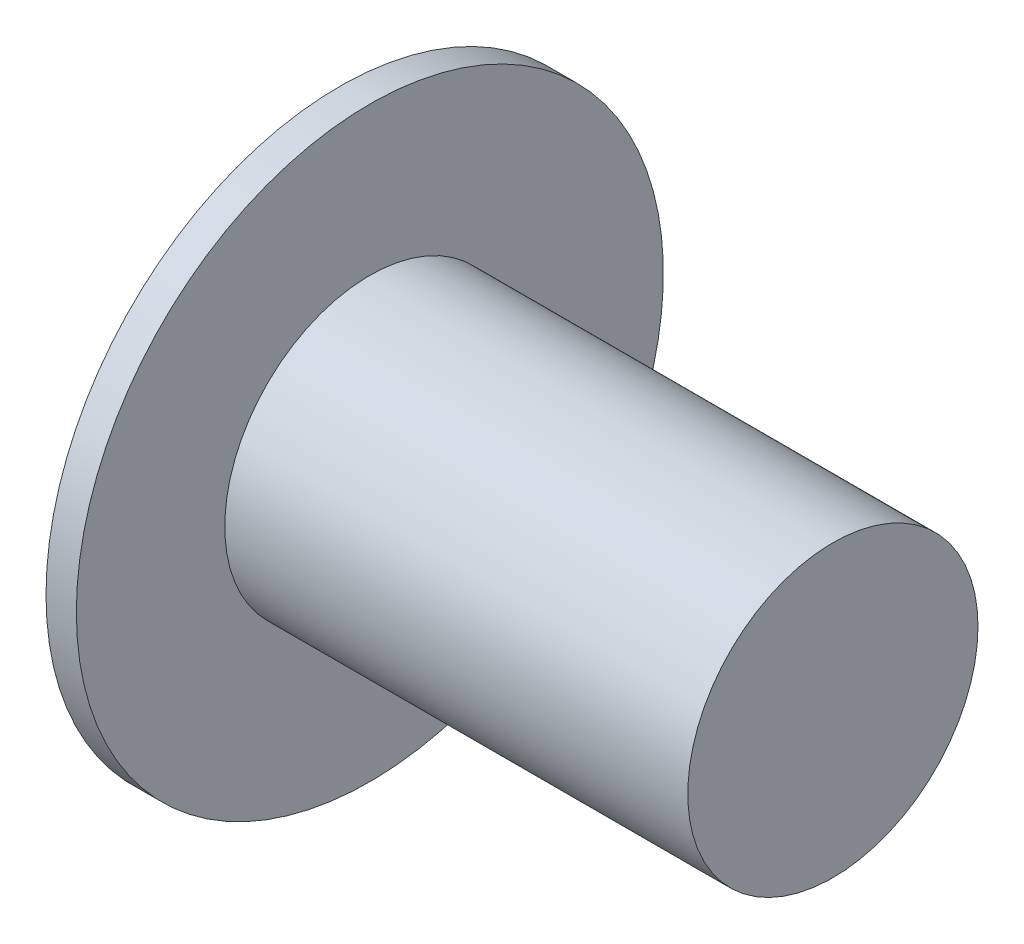
SolidWorks part; units mm, degrees
ref_plane "Front Plane" through (0, 0, 0) normal (0, 0, 1) x (1, 0, 0)
ref_plane "Top Plane" through (0, 0, 0) normal (0, 1, 0) x (1, 0, 0)
ref_plane "Right Plane" through (0, 0, 0) normal (1, 0, 0) x (0, 0, -1)
sketch "Sketch2" plane through (0, 0, 0) normal (1, 0, 0) x (0, 0, -1)
  circle A0 centre (0, 0) radius 11
  dimension "D1" = 22
extrude "Boss-Extrude2" add sketch "Sketch2" along normal blind 35.1
sketch "Sketch3" plane through (0, 0, 0) normal (-1, 0, 0) x (0, 0, 1)
  circle A0 centre (0, 0) radius 22.25
  dimension "D1" = 44.5
extrude "Boss-Extrude3" add sketch "Sketch3" along normal blind 2.3
sketch "Sketch4" plane through (-2.3, 0, 0) normal (-1, 0, 0) x (0, 0, 1)
  circle A0 centre (0, 0) radius 11
  dimension "D1" = 22
extrude "Boss-Extrude4" add sketch "Sketch4" along normal blind 5
sketch "Sketch5" plane through (-7.3, 0, 0) normal (-1, 0, 0) x (0, 0, 1)
  circle A0 centre (0, 0) radius 3.9
  dimension "D1" = 7.8
extrude "Boss-Extrude5" add sketch "Sketch5" along normal blind 7.54
